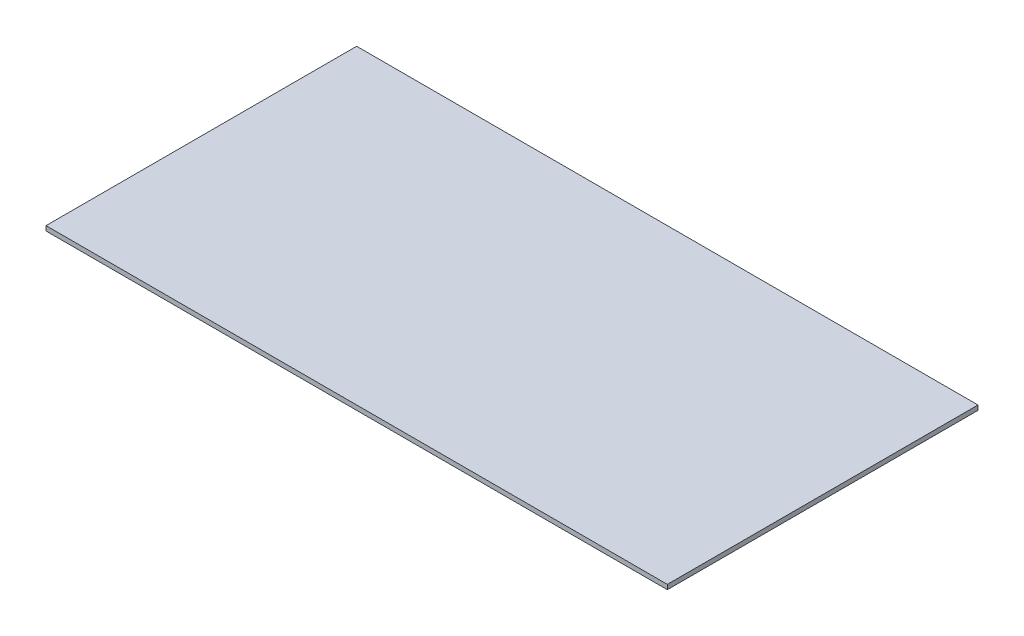
SolidWorks part; units mm, degrees
ref_plane "Front Plane" through (0, 0, 0) normal (0, 0, 1) x (1, 0, 0)
ref_plane "Top Plane" through (0, 0, 0) normal (0, 1, 0) x (1, 0, 0)
ref_plane "Right Plane" through (0, 0, 0) normal (1, 0, 0) x (0, 0, -1)
sketch "Sketch1" plane through (0, 0, 0) normal (0, 1, 0) x (1, 0, 0)
  line L1 (0, 0) -> (400, 0)
  line L2 (0, 0) -> (0, 200)
  line L3 (0, 200) -> (400, 200)
  line L4 (400, 0) -> (400, 200)
  dimension "D1" = 200
  dimension "D2" = 400
extrude "Boss-Extrude1" add sketch "Sketch1" along normal blind 3
